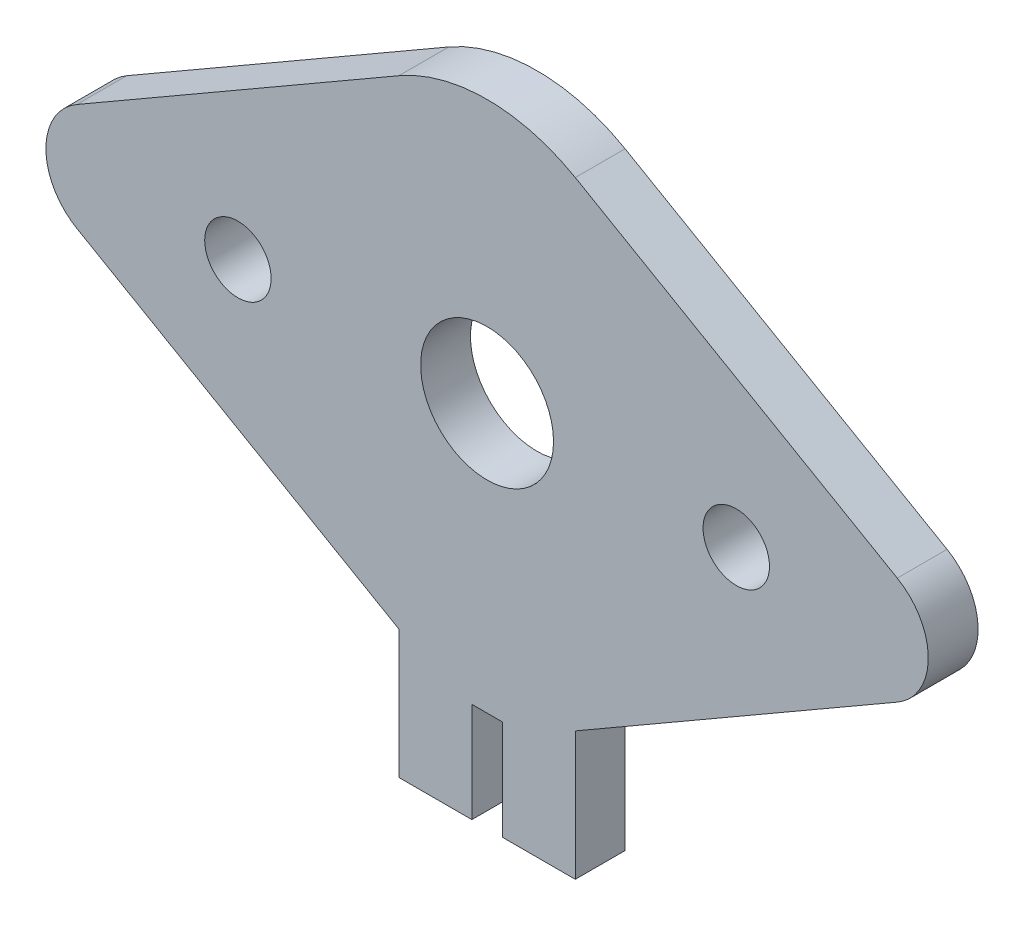
SolidWorks part; units mm, degrees
ref_plane "前视基准面" through (0, 0, 0) normal (0, 0, 1) x (1, 0, 0)
ref_plane "上视基准面" through (0, 0, 0) normal (0, 1, 0) x (1, 0, 0)
ref_plane "右视基准面" through (0, 0, 0) normal (1, 0, 0) x (0, 0, -1)
sketch "草图1" plane through (0, 0, 0) normal (0, 0, 1) x (1, 0, 0)
  line L0 (0, 0) -> (15, 0)
  line L1 (0, -1000) -> (0, 49000) construction
  line L2 (5.3093, 14.4241) -> (24.6931, 3.2329)
  line L3 (-1000, 0) -> (49000, 0) construction
  line L4 (-5.3093, 14.4241) -> (-24.6931, 3.2329)
  line L5 (5.3093, -14.4241) -> (24.6931, -3.2329)
  line L6 (-5.3093, -14.4241) -> (-24.6931, -3.2329)
  line L7 (-5.3093, -14.4241) -> (-5.3093, -22.1621)
  line L8 (-5.3093, -22.1621) -> (-0.9163, -22.1621)
  line L9 (-0.9163, -22.1621) -> (-0.9163, -16.1508)
  line L10 (-0.9163, -16.1508) -> (0.9163, -16.1508)
  line L11 (0.9163, -22.1621) -> (0.9163, -16.1508)
  line L12 (5.3093, -22.1621) -> (0.9163, -22.1621)
  line L13 (5.3093, -14.4241) -> (5.3093, -22.1621)
  circle A0 centre (0, 0) radius 4
  circle A1 centre (15, 0) radius 2
  circle A2 centre (-15, 0) radius 2
  arc A3 (-5.3093, 14.4241) -> (5.3093, 14.4241) centre (0, 5.2282) cw
  arc A4 (24.6931, 3.2329) -> (24.6931, -3.2329) centre (22.8266, 0) cw
  arc A5 (-24.6931, 3.2329) -> (-24.6931, -3.2329) centre (-22.8266, 0) ccw
  point P27 (0, -16.1508)
  dimension "D1" = 8
  dimension "D3" = 4
  dimension "D2" = 15
extrude "凸台-拉伸1" add sketch "草图1" along normal blind 3 contours L4 A5 L6 L7 L8 L9 L10 L11 L12 L13 L5 A4 L2 A3 | A2 | A0 | A1
